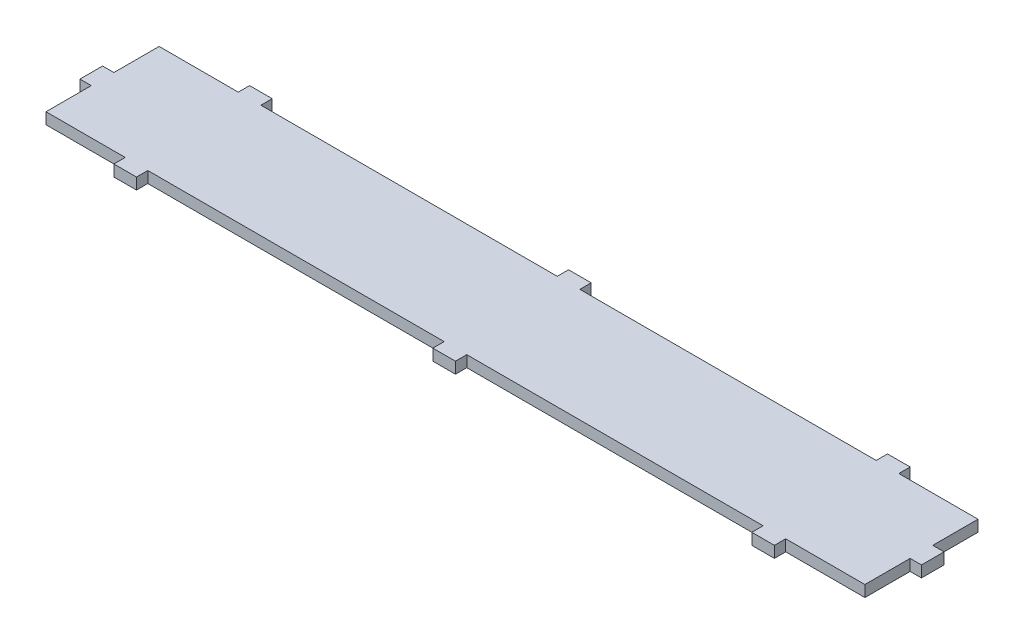
SolidWorks part; units mm, degrees
ref_plane "Front Plane" through (0, 0, 0) normal (0, 0, 1) x (1, 0, 0)
ref_plane "Top Plane" through (0, 0, 0) normal (0, 1, 0) x (1, 0, 0)
ref_plane "Right Plane" through (0, 0, 0) normal (1, 0, 0) x (0, 0, -1)
sketch "Sketch1" plane through (0, 0, 0) normal (0, 1, 0) x (1, 0, 0)
  line L0 (-181, 25) -> (-181, 5)
  line L1 (146, 30) -> (136, 30)
  line L4 (-186, 5) -> (-186, -5)
  line L7 (-181, 5) -> (-186, 5)
  line L8 (-181, -5) -> (-186, -5)
  line L9 (-181, -5) -> (-181, -25)
  line L10 (186, 5) -> (181, 5)
  line L11 (186, -5) -> (181, -5)
  line L12 (-146, 30) -> (-146, 25)
  line L13 (-136, 25) -> (-5, 25)
  line L14 (-136, 25) -> (-136, 30)
  line L15 (146, 30) -> (146, 25)
  line L16 (146, 25) -> (181, 25)
  line L17 (136, 25) -> (136, 30)
  line L18 (5, 25) -> (136, 25)
  line L19 (5, 25) -> (5, 30)
  line L20 (-5, 25) -> (-5, 30)
  line L21 (-181, 25) -> (-146, 25)
  line L22 (5, 30) -> (-5, 30)
  line L23 (-136, 30) -> (-146, 30)
  line L24 (186, 5) -> (186, -5)
  line L26 (-136, -30) -> (-146, -30)
  line L28 (5, -30) -> (-5, -30)
  line L29 (-181, -25) -> (-146, -25)
  line L30 (-5, -25) -> (-5, -30)
  line L31 (5, -25) -> (5, -30)
  line L32 (5, -25) -> (136, -25)
  line L35 (136, -25) -> (136, -30)
  line L36 (146, -25) -> (181, -25)
  line L37 (146, -30) -> (146, -25)
  line L38 (-136, -25) -> (-136, -30)
  line L39 (-136, -25) -> (-5, -25)
  line L40 (181, 5) -> (181, 25)
  line L41 (181, -5) -> (181, -25)
  line L42 (-146, -30) -> (-146, -25)
  line L43 (146, -30) -> (136, -30)
  point P0 (0, 0)
  point P16 (0, 30)
  point P19 (-186, 0)
  point P24 (186, 0)
  dimension "D1" = 5
  dimension "D2" = 35
  dimension "D3" = 10
  dimension "D4" = 10
  dimension "D5" = 372
  dimension "D6" = 10
  dimension "D7" = 5
  dimension "D8" = 20
  dimension "D9" = 10
  dimension "D10" = 10
  dimension "D11" = 5
  dimension "D12" = 5
  dimension "D16" = 35
  dimension "D20" = 5
  dimension "D23" = 5
  dimension "D24" = 131
  dimension "D25" = 131
  dimension "D28" = 20
extrude "Boss-Extrude1" add sketch "Sketch1" along normal blind 5
